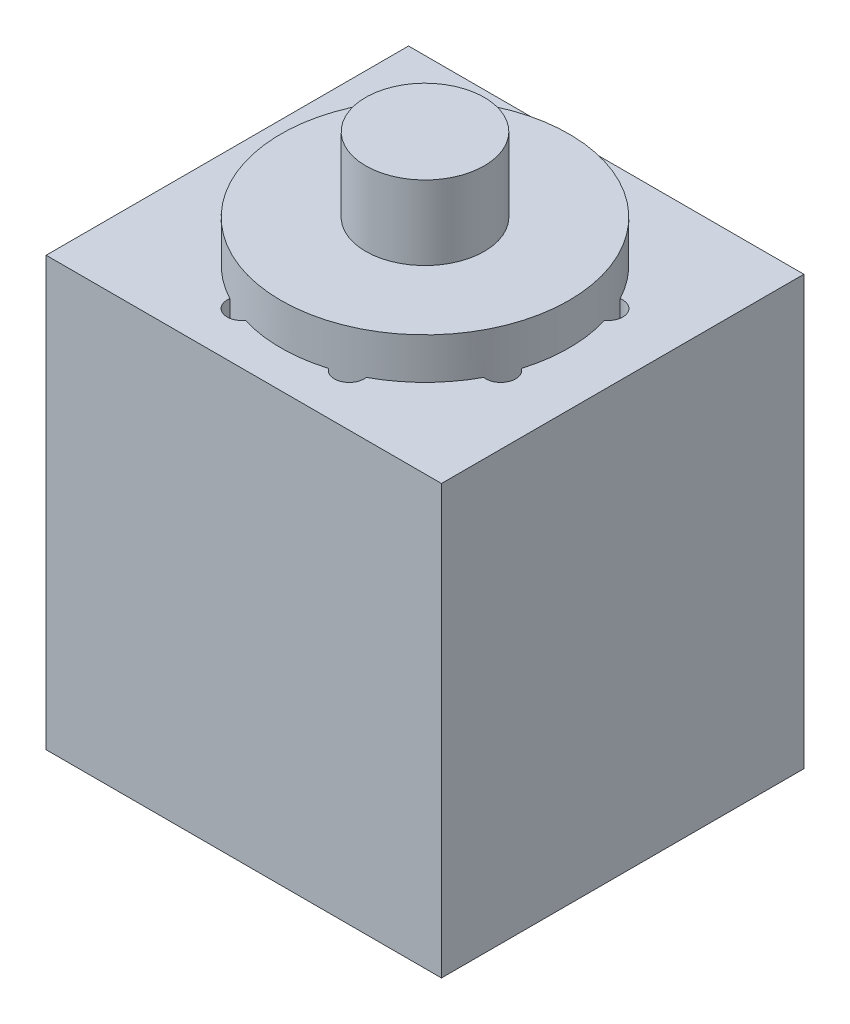
SolidWorks part; units mm, degrees
ref_plane "前视基准面" through (0, 0, 0) normal (0, 0, 1) x (1, 0, 0)
ref_plane "上视基准面" through (0, 0, 0) normal (0, 1, 0) x (1, 0, 0)
ref_plane "右视基准面" through (0, 0, 0) normal (1, 0, 0) x (0, 0, -1)
other "Configuration Table"
sketch "01_Housing_Profile" plane through (0, 0, 0) normal (0, 1, 0) x (1, 0, 0)
  line L1 (-120, -110) -> (120, -110)
  line L2 (-120, -110) -> (-120, 110)
  line L3 (-120, 110) -> (120, 110)
  line L4 (120, -110) -> (120, 110)
  line L5 (-120, -110) -> (120, 110) construction
  line L6 (-120, 110) -> (120, -110) construction
  circle A0 centre (78.5298, 32.5281) radius 9
  circle A1 centre (32.5281, 78.5298) radius 9
  circle A2 centre (-32.5281, 78.5298) radius 9
  circle A3 centre (-78.5298, 32.5281) radius 9
  circle A4 centre (-78.5298, -32.5281) radius 9
  circle A5 centre (-32.5281, -78.5298) radius 9
  circle A6 centre (32.5281, -78.5298) radius 9
  circle A7 centre (78.5298, -32.5281) radius 9
  point P0 (0, 0)
extrude "01_Housing_Block" add sketch "01_Housing_Profile" along normal blind 260
sketch "02_Face_Boss_Profile" plane through (0, 0, 0) normal (0, 1, 0) x (1, 0, 0)
  circle A0 centre (0, 0) radius 87.5
extrude "02_Face_Locating_Boss" add sketch "02_Face_Boss_Profile" along normal blind 285
sketch "03_Output_Shaft_Profile" plane through (0, 0, 0) normal (0, 1, 0) x (1, 0, 0)
  circle A0 centre (0, 0) radius 36
extrude "03_Output_Shaft" add sketch "03_Output_Shaft_Profile" along normal blind 330
